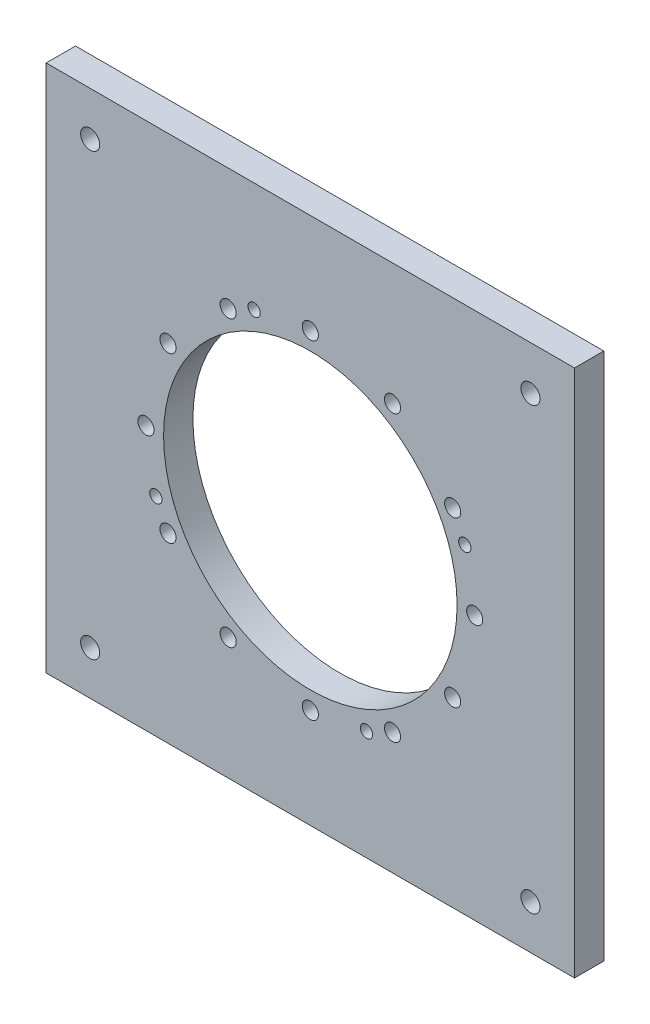
SolidWorks part; units mm, degrees
material "6061-T6 (SS)"
ref_plane "前视基准面" through (0, 0, 0) normal (0, 0, 1) x (1, 0, 0)
ref_plane "上视基准面" through (0, 0, 0) normal (0, 1, 0) x (1, 0, 0)
ref_plane "右视基准面" through (0, 0, 0) normal (1, 0, 0) x (0, 0, -1)
other "Configuration Table"
sketch "草图1" plane through (0, 0, 0) normal (0, 0, 1) x (1, 0, 0)
  line L0 (-90, -90) -> (90, -90)
  line L1 (90, -90) -> (90, 90)
  line L2 (90, 90) -> (-90, 90)
  line L3 (-90, 90) -> (-90, -90)
extrude "凸台-拉伸1" add sketch "草图1" along normal blind 10
sketch "草图2" plane through (0, 0, 0) normal (0, 0, -1) x (-1, 0, 0)
  circle A0 centre (0, 0) radius 50
  circle A1 centre (-56, 0) radius 2.75
  circle A2 centre (-48.4974, 28) radius 2.75
  circle A3 centre (-28, 48.4974) radius 2.75
  circle A4 centre (0, 56) radius 2.75
  circle A5 centre (28, 48.4974) radius 2.75
  circle A6 centre (48.4974, 28) radius 2.75
  circle A7 centre (56, 0) radius 2.75
  circle A8 centre (48.4974, -28) radius 2.75
  circle A9 centre (28, -48.4974) radius 2.75
  circle A10 centre (0, -56) radius 2.75
  circle A11 centre (-28, -48.4974) radius 2.75
  circle A12 centre (-48.4974, -28) radius 2.75
  circle A13 centre (-52.6228, 19.1531) radius 2.1
  circle A14 centre (19.1531, 52.6228) radius 2.1
  circle A15 centre (52.6228, -19.1531) radius 2.1
  circle A16 centre (-19.1531, -52.6228) radius 2.1
  circle A17 centre (75, -75) radius 3.25
  circle A18 centre (75, 75) radius 3.25
  circle A19 centre (-75, -75) radius 3.25
  circle A20 centre (-75, 75) radius 3.25
extrude "切除-拉伸1" cut sketch "草图2" against normal blind 11
